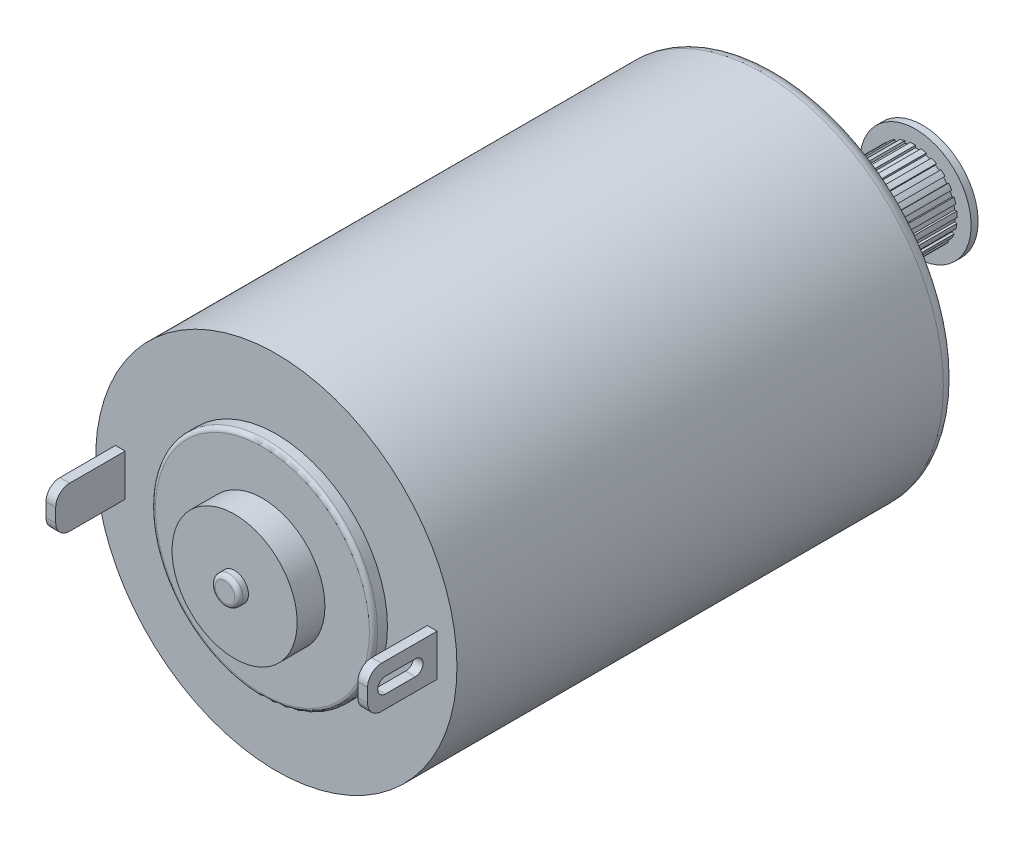
SolidWorks part; units mm, degrees
ref_plane "Front Plane" through (0, 0, 0) normal (0, 0, 1) x (1, 0, 0)
ref_plane "Top Plane" through (0, 0, 0) normal (0, 1, 0) x (1, 0, 0)
ref_plane "Right Plane" through (0, 0, 0) normal (1, 0, 0) x (0, 0, -1)
sketch "Sketch1" plane through (0, 0, 0) normal (0, 0, 1) x (1, 0, 0)
  line L0 (0, 23.2037) -> (0, -22.0459) construction
  line L1 (-45.4426, 0) -> (40.1361, 0) construction
  circle A0 centre (0, 0) radius 13
  dimension "D1" = 26
extrude "Boss-Extrude1" add sketch "Sketch1" along normal blind 36
sketch "Sketch2" plane through (0, 0, 36) normal (0, 0, 1) x (1, 0, 0)
  line L0 (0, 15.3076) -> (0, -15.444) construction
  line L1 (-15.2053, 0) -> (15.4099, 0) construction
  circle A0 centre (0, 0) radius 8
  dimension "D1" = 16
extrude "Boss-Extrude2" add sketch "Sketch2" along normal blind 1
sketch "Sketch3" plane through (0, 0, 37) normal (0, 0, 1) x (1, 0, 0)
  line L0 (0, 10.2791) -> (0, -9.4899) construction
  line L1 (-9.0756, 0) -> (9.0756, 0) construction
  circle A0 centre (0, 0) radius 4.5
  dimension "D1" = 9
extrude "Boss-Extrude3" add sketch "Sketch3" along normal blind 2
sketch "Sketch4" plane through (0, 0, 39) normal (0, 0, 1) x (1, 0, 0)
  line L0 (0, 5.2283) -> (0, -5.5045) construction
  line L1 (-5.4848, 0) -> (5.3664, 0) construction
  line L2 (5.3664, 0) -> (0, 0) construction
  circle A0 centre (0, 0) radius 1
  dimension "D1" = 2
extrude "Boss-Extrude4" add sketch "Sketch4" along normal blind 0.7
fillet "Fillet1" radius 0.3 1 edges at (1, 0, 39.7)
fillet "Fillet2" radius 0.3 1 edges at (8, 0, 37)
sketch "Sketch5" plane through (0, 0, 36) normal (0, 0, 1) x (1, 0, 0)
  line L0 (0, 13.6726) -> (0, -13.712) construction
  line L1 (-14.0475, 0) -> (14.2053, 0) construction
  line L2 (-10.871, -1.5) -> (-11.571, -1.5)
  line L3 (10.871, 1.5) -> (11.571, 1.5)
  line L4 (10.871, 1.5) -> (10.871, -1.5)
  line L5 (10.871, -1.5) -> (11.571, -1.5)
  line L6 (11.571, 1.5) -> (11.571, -1.5)
  line L7 (-11.571, 1.5) -> (-11.571, -1.5)
  line L8 (-10.871, 1.5) -> (-11.571, 1.5)
  line L9 (-10.871, 1.5) -> (-10.871, -1.5)
  dimension "D1" = 0.7
  dimension "D2" = 3
extrude "Boss-Extrude5" add sketch "Sketch5" along normal blind 5
fillet "Fillet3" radius 1 2 edges at (11.221, -1.5, 41) (11.221, 1.5, 41)
fillet "Fillet4" radius 1 2 edges at (-11.221, -1.5, 41) (-11.221, 1.5, 41)
sketch "Sketch7" plane through (11.571, 0, 0) normal (1, 0, 0) x (0, 0, -1)
  line L0 (-37.5688, 0) -> (-39.7171, 0) construction
  line L1 (-37.5688, -0.5566) -> (-39.7171, -0.5566)
  line L2 (-37.5688, 0.5566) -> (-39.7171, 0.5566)
  arc A0 (-37.5688, -0.5566) -> (-37.5688, 0.5566) centre (-37.5688, 0) ccw
  arc A1 (-39.7171, 0.5566) -> (-39.7171, -0.5566) centre (-39.7171, 0) ccw
  point P3 (-38.643, 0)
extrude "Cut-Extrude1" cut sketch "Sketch7" against normal blind 5
sketch "Sketch8" plane through (0, 0, 0) normal (0, 0, -1) x (-1, 0, 0)
  line L0 (0, 13.9488) -> (0, -13.8304) construction
  line L1 (-13.8896, 0) -> (14.008, 0) construction
  circle A0 centre (0, 0) radius 4.5
  dimension "D1" = 9
extrude "Boss-Extrude6" add sketch "Sketch8" along normal blind 2
sketch "Sketch9" plane through (0, 0, -2) normal (0, 0, -1) x (-1, 0, 0)
  line L0 (0, 5.4651) -> (0, -5.9386) construction
  line L1 (-6.3135, 0) -> (5.8794, 0) construction
  circle A0 centre (0, 0) radius 1
  dimension "D1" = 2
extrude "Boss-Extrude7" add sketch "Sketch9" along normal blind 2
sketch "Sketch10" plane through (0, 0, -4) normal (0, 0, -1) x (-1, 0, 0)
  line L0 (0, 1.3611) -> (0, -1.6351) construction
  line L1 (-1.6739, 0) -> (1.5097, 0) construction
  circle A0 centre (0, 0) radius 3
  dimension "D1" = 6
extrude "Boss-Extrude8" add sketch "Sketch10" along normal blind 6
sketch "Sketch11" plane through (0, 0, -10) normal (0, 0, -1) x (-1, 0, 0)
  line L0 (0, 3.4496) -> (0, -3.455) construction
  line L1 (-3.4063, 0) -> (3.2265, 0) construction
  line L2 (0, 3.0358) -> (0, 2.8427)
  line L3 (0, 0) -> (-0.371, 2.8184) construction
  line L4 (-0.371, 2.8184) -> (-0.4119, 3.1285) construction
  line L5 (-0.371, 2.8184) -> (-0.4084, 3.1019)
  line L6 (-0.4084, 3.1019) -> (0, 3.0358)
  line L7 (0.7857, 2.9324) -> (0.7357, 2.7458)
  line L8 (0.371, 2.8184) -> (0.4084, 3.1019)
  line L9 (0.4084, 3.1019) -> (0.7857, 2.9324)
  line L10 (1.5179, 2.6291) -> (1.4213, 2.4618)
  line L11 (1.0878, 2.6263) -> (1.1973, 2.8905)
  line L12 (1.1973, 2.8905) -> (1.5179, 2.6291)
  line L13 (2.1466, 2.1466) -> (2.0101, 2.0101)
  line L14 (1.7305, 2.2552) -> (1.9046, 2.4821)
  line L15 (1.9046, 2.4821) -> (2.1466, 2.1466)
  line L16 (2.6291, 1.5179) -> (2.4618, 1.4213)
  line L17 (2.2552, 1.7305) -> (2.4821, 1.9046)
  line L18 (2.4821, 1.9046) -> (2.6291, 1.5179)
  line L19 (2.9324, 0.7857) -> (2.7458, 0.7357)
  line L20 (2.6263, 1.0878) -> (2.8905, 1.1973)
  line L21 (2.8905, 1.1973) -> (2.9324, 0.7857)
  line L22 (3.0358, 0) -> (2.8427, 0)
  line L23 (2.8184, 0.371) -> (3.1019, 0.4084)
  line L24 (3.1019, 0.4084) -> (3.0358, 0)
  line L25 (2.9324, -0.7857) -> (2.7458, -0.7357)
  line L26 (2.8184, -0.371) -> (3.1019, -0.4084)
  line L27 (3.1019, -0.4084) -> (2.9324, -0.7857)
  line L28 (2.6291, -1.5179) -> (2.4618, -1.4213)
  line L29 (2.6263, -1.0878) -> (2.8905, -1.1973)
  line L30 (2.8905, -1.1973) -> (2.6291, -1.5179)
  line L31 (2.1466, -2.1466) -> (2.0101, -2.0101)
  line L32 (2.2552, -1.7305) -> (2.4821, -1.9046)
  line L33 (2.4821, -1.9046) -> (2.1466, -2.1466)
  line L34 (1.5179, -2.6291) -> (1.4213, -2.4618)
  line L35 (1.7305, -2.2552) -> (1.9046, -2.4821)
  line L36 (1.9046, -2.4821) -> (1.5179, -2.6291)
  line L37 (0.7857, -2.9324) -> (0.7357, -2.7458)
  line L38 (1.0878, -2.6263) -> (1.1973, -2.8905)
  line L39 (1.1973, -2.8905) -> (0.7857, -2.9324)
  line L40 (0, -3.0358) -> (0, -2.8427)
  line L41 (0.371, -2.8184) -> (0.4084, -3.1019)
  line L42 (0.4084, -3.1019) -> (0, -3.0358)
  line L43 (-0.7857, -2.9324) -> (-0.7357, -2.7458)
  line L44 (-0.371, -2.8184) -> (-0.4084, -3.1019)
  line L45 (-0.4084, -3.1019) -> (-0.7857, -2.9324)
  line L46 (-1.5179, -2.6291) -> (-1.4213, -2.4618)
  line L47 (-1.0878, -2.6263) -> (-1.1973, -2.8905)
  line L48 (-1.1973, -2.8905) -> (-1.5179, -2.6291)
  line L49 (-2.1466, -2.1466) -> (-2.0101, -2.0101)
  line L50 (-1.7305, -2.2552) -> (-1.9046, -2.4821)
  line L51 (-1.9046, -2.4821) -> (-2.1466, -2.1466)
  line L52 (-2.6291, -1.5179) -> (-2.4618, -1.4213)
  line L53 (-2.2552, -1.7305) -> (-2.4821, -1.9046)
  line L54 (-2.4821, -1.9046) -> (-2.6291, -1.5179)
  line L55 (-2.9324, -0.7857) -> (-2.7458, -0.7357)
  line L56 (-2.6263, -1.0878) -> (-2.8905, -1.1973)
  line L57 (-2.8905, -1.1973) -> (-2.9324, -0.7857)
  line L58 (-3.0358, 0) -> (-2.8427, 0)
  line L59 (-2.8184, -0.371) -> (-3.1019, -0.4084)
  line L60 (-3.1019, -0.4084) -> (-3.0358, 0)
  line L61 (-2.9324, 0.7857) -> (-2.7458, 0.7357)
  line L62 (-2.8184, 0.371) -> (-3.1019, 0.4084)
  line L63 (-3.1019, 0.4084) -> (-2.9324, 0.7857)
  line L64 (-2.6291, 1.5179) -> (-2.4618, 1.4213)
  line L65 (-2.6263, 1.0878) -> (-2.8905, 1.1973)
  line L66 (-2.8905, 1.1973) -> (-2.6291, 1.5179)
  line L67 (-2.1466, 2.1466) -> (-2.0101, 2.0101)
  line L68 (-2.2552, 1.7305) -> (-2.4821, 1.9046)
  line L69 (-2.4821, 1.9046) -> (-2.1466, 2.1466)
  line L70 (-1.5179, 2.6291) -> (-1.4213, 2.4618)
  line L71 (-1.7305, 2.2552) -> (-1.9046, 2.4821)
  line L72 (-1.9046, 2.4821) -> (-1.5179, 2.6291)
  line L73 (-0.7857, 2.9324) -> (-0.7357, 2.7458)
  line L74 (-1.0878, 2.6263) -> (-1.1973, 2.8905)
  line L75 (-1.1973, 2.8905) -> (-0.7857, 2.9324)
  arc A0 (0, 2.8427) -> (-0.371, 2.8184) centre (0, 0) ccw
  arc A1 (0.7357, 2.7458) -> (0.371, 2.8184) centre (0, 0) ccw
  arc A2 (1.4213, 2.4618) -> (1.0878, 2.6263) centre (0, 0) ccw
  arc A3 (2.0101, 2.0101) -> (1.7305, 2.2552) centre (0, 0) ccw
  arc A4 (2.4618, 1.4213) -> (2.2552, 1.7305) centre (0, 0) ccw
  arc A5 (2.7458, 0.7357) -> (2.6263, 1.0878) centre (0, 0) ccw
  arc A6 (2.8427, 0) -> (2.8184, 0.371) centre (0, 0) ccw
  arc A7 (2.7458, -0.7357) -> (2.8184, -0.371) centre (0, 0) ccw
  arc A8 (2.4618, -1.4213) -> (2.6263, -1.0878) centre (0, 0) ccw
  arc A9 (2.0101, -2.0101) -> (2.2552, -1.7305) centre (0, 0) ccw
  arc A10 (1.4213, -2.4618) -> (1.7305, -2.2552) centre (0, 0) ccw
  arc A11 (0.7357, -2.7458) -> (1.0878, -2.6263) centre (0, 0) ccw
  arc A12 (0, -2.8427) -> (0.371, -2.8184) centre (0, 0) ccw
  arc A13 (-0.7357, -2.7458) -> (-0.371, -2.8184) centre (0, 0) ccw
  arc A14 (-1.4213, -2.4618) -> (-1.0878, -2.6263) centre (0, 0) ccw
  arc A15 (-2.0101, -2.0101) -> (-1.7305, -2.2552) centre (0, 0) ccw
  arc A16 (-2.4618, -1.4213) -> (-2.2552, -1.7305) centre (0, 0) ccw
  arc A17 (-2.7458, -0.7357) -> (-2.6263, -1.0878) centre (0, 0) ccw
  arc A18 (-2.8427, 0) -> (-2.8184, -0.371) centre (0, 0) ccw
  arc A19 (-2.7458, 0.7357) -> (-2.8184, 0.371) centre (0, 0) ccw
  arc A20 (-2.4618, 1.4213) -> (-2.6263, 1.0878) centre (0, 0) ccw
  arc A21 (-2.0101, 2.0101) -> (-2.2552, 1.7305) centre (0, 0) ccw
  arc A22 (-1.4213, 2.4618) -> (-1.7305, 2.2552) centre (0, 0) ccw
  arc A23 (-0.7357, 2.7458) -> (-1.0878, 2.6263) centre (0, 0) ccw
  point P105 (0, 0)
  dimension "D1" = 24
extrude "Cut-Extrude2" cut sketch "Sketch11" against normal up to surface (8 mm away) up to face at (-4.5, 0, -2)
sketch "Sketch12" plane through (0, 0, -10) normal (0, 0, -1) x (-1, 0, 0)
  line L0 (0, 3.1188) -> (0, -3.1912) construction
  line L1 (-3.3012, 0) -> (3.2754, 0) construction
  circle A0 centre (0, 0) radius 4
  dimension "D1" = 8
extrude "Boss-Extrude9" add sketch "Sketch12" along normal blind 0.5
sketch "Sketch13" plane through (0, 0, -10.5) normal (0, 0, -1) x (-1, 0, 0)
  line L0 (0, 4.9691) -> (0, -5.1839) construction
  line L1 (-5.1067, 0) -> (5.0463, 0) construction
  circle A0 centre (0, 0) radius 1
  dimension "D1" = 2
extrude "Cut-Extrude3" cut sketch "Sketch13" against normal blind 1
fillet "Fillet5" radius 1 1 edges at (13, 0, 0)
